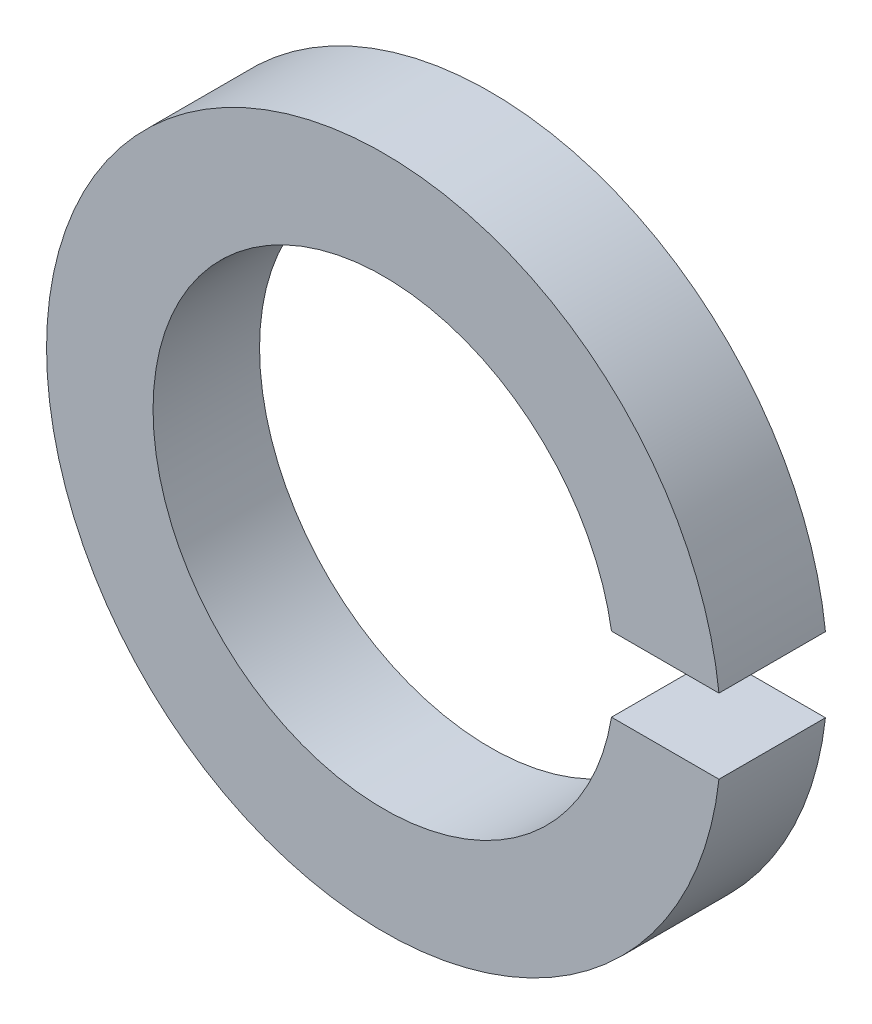
SolidWorks part; units mm, degrees
ref_plane "Спереди" through (0, 0, 0) normal (0, 0, 1) x (1, 0, 0)
ref_plane "Сверху" through (0, 0, 0) normal (0, 1, 0) x (1, 0, 0)
ref_plane "Справа" through (0, 0, 0) normal (1, 0, 0) x (0, 0, -1)
sketch "Эскиз1" plane through (0, 0, 0) normal (0, 0, 1) x (1, 0, 0)
  circle A0 centre (0, 0) radius 1.9
  circle A1 centre (0, 0) radius 1.3
  dimension "D1" = 3.8
  dimension "D2" = 2.6
extrude "Вытянуть1" add sketch "Эскиз1" along normal blind 0.6
sketch "Эскиз2" plane through (0, 0, 0.6) normal (0, 0, 1) x (1, 0, 0)
  line L0 (0, 0) -> (0.123, 0) construction
  line L1 (1.9, 0) -> (-1.9, 0) construction
  line L3 (1.0718, 0.21) -> (3.3184, 0.21)
  line L4 (1.0718, 0.21) -> (1.0718, -0.21)
  line L5 (1.0718, -0.21) -> (3.3184, -0.21)
  line L6 (3.3184, 0.21) -> (3.3184, -0.21)
  circle A0 centre (0, 0) radius 1.9 construction
  dimension "D1" = 0.21
  dimension "D2" = 0.42
extrude "Вырез-Вытянуть1" cut sketch "Эскиз2" against normal through all
